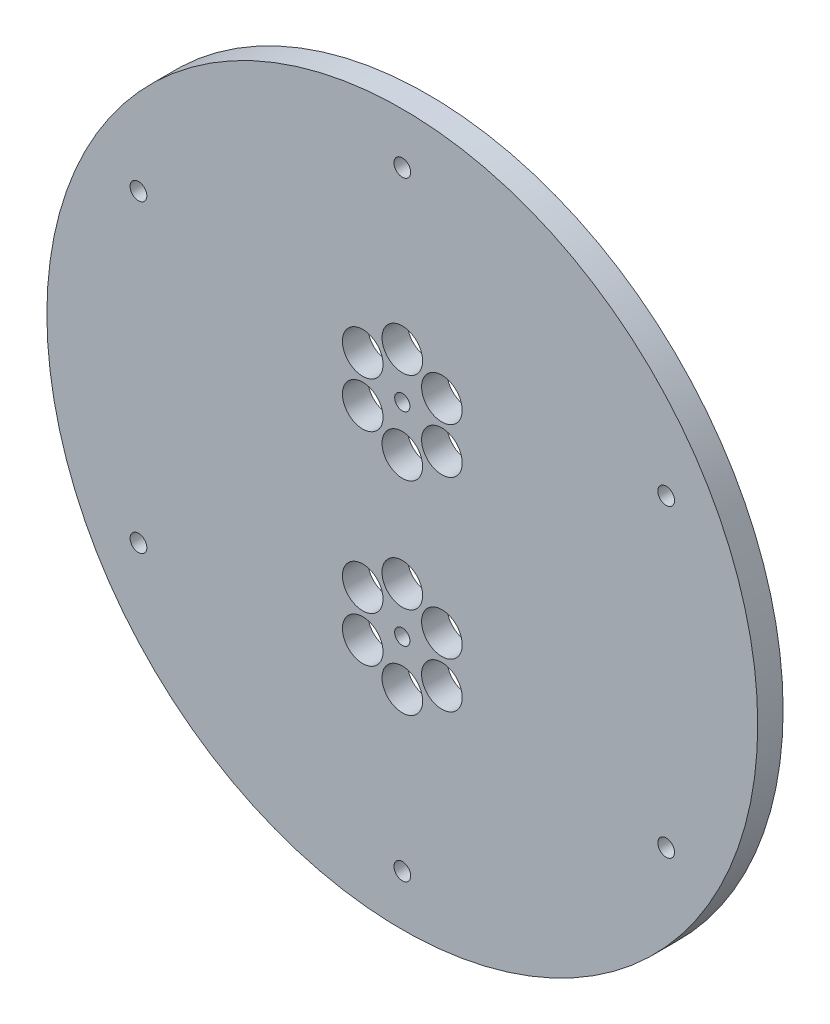
SolidWorks part; units mm, degrees
ref_plane "Front Plane" through (0, 0, 0) normal (0, 0, 1) x (1, 0, 0)
ref_plane "Top Plane" through (0, 0, 0) normal (0, 1, 0) x (1, 0, 0)
ref_plane "Right Plane" through (0, 0, 0) normal (1, 0, 0) x (0, 0, -1)
sketch "Sketch1" plane through (0, 0, 0) normal (0, 0, 1) x (1, 0, 0)
  line L0 (0, 70) -> (0, -70) construction
  line L1 (0, 0) -> (70, 0) construction
  circle A0 centre (0, 0) radius 70
  circle A2 centre (0, 0) radius 60 construction
  circle A3 centre (0, 60) radius 1.65
  circle A4 centre (51.9615, 30) radius 1.65
  circle A5 centre (51.9615, -30) radius 1.65
  circle A6 centre (0, -60) radius 1.65
  circle A7 centre (-51.9615, -30) radius 1.65
  circle A8 centre (-51.9615, 30) radius 1.65
  circle A9 centre (0, 0) radius 9 construction
  circle A10 centre (0, 0) radius 1.5 construction
  circle A11 centre (0, 9) radius 4 construction
  circle A12 centre (7.7942, 4.5) radius 4 construction
  circle A13 centre (7.7942, -4.5) radius 4 construction
  circle A14 centre (0, -9) radius 4 construction
  circle A15 centre (-7.7942, -4.5) radius 4 construction
  circle A16 centre (-7.7942, 4.5) radius 4 construction
  circle A17 centre (0, 20) radius 9 construction
  circle A18 centre (0, 29) radius 4
  circle A19 centre (7.7942, 24.5) radius 4
  circle A20 centre (7.7942, 15.5) radius 4
  circle A21 centre (0, 11) radius 4
  circle A22 centre (-7.7942, 15.5) radius 4
  circle A23 centre (-7.7942, 24.5) radius 4
  circle A24 centre (0, 20) radius 1.5
  circle A25 centre (7.7942, -15.5) radius 4
  circle A26 centre (0, -11) radius 4
  circle A27 centre (-7.7942, -15.5) radius 4
  circle A28 centre (0, -20) radius 1.5
  circle A29 centre (-7.7942, -24.5) radius 4
  circle A30 centre (0, -29) radius 4
  circle A31 centre (7.7942, -24.5) radius 4
  circle A32 centre (0, 0) radius 13 construction
  point P19 (0, 0)
  point P33 (0, 0)
  point P51 (0, 20)
  dimension "D1" = 140
  dimension "D2" = 18
  dimension "D3" = 10
  dimension "D4" = 3.3
  dimension "D6" = 6
  dimension "D7" = 8
  dimension "D8" = 3
  dimension "D9" = 18
  dimension "D12" = 26
  dimension "D10" = 20
  dimension "D5" = 6
  dimension "D11" = 6
extrude "Boss-Extrude1" add sketch "Sketch1" along normal blind 5
